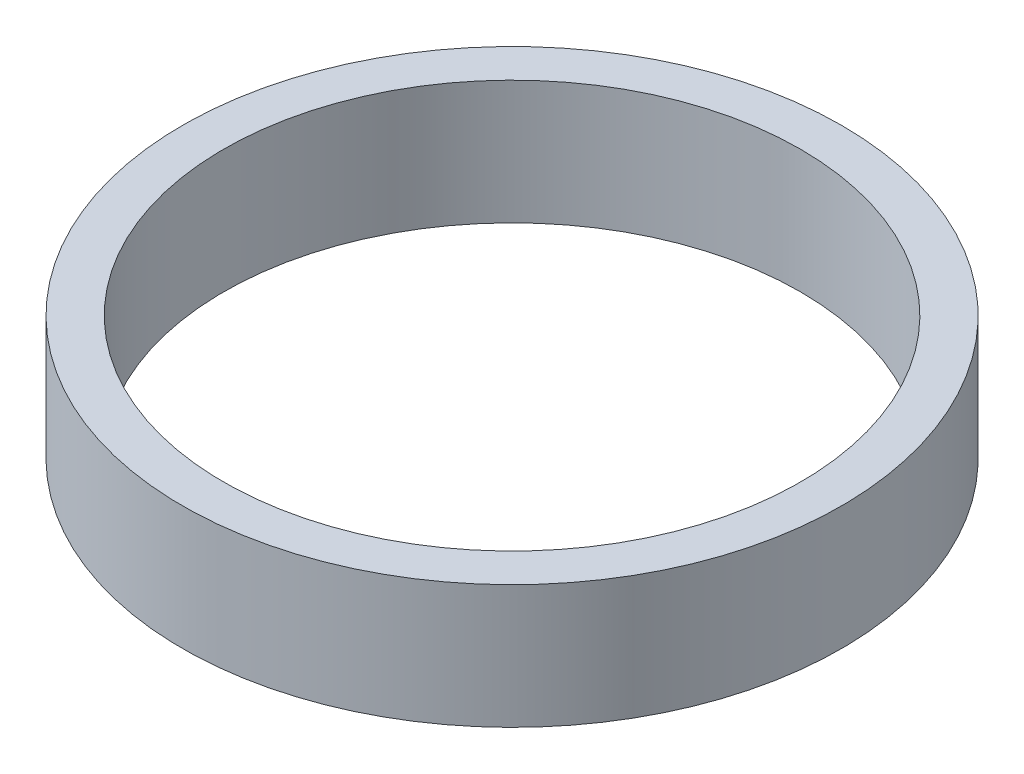
SolidWorks part; units mm, degrees
ref_plane "Front Plane" through (0, 0, 0) normal (0, 0, 1) x (1, 0, 0)
ref_plane "Top Plane" through (0, 0, 0) normal (0, 1, 0) x (1, 0, 0)
ref_plane "Right Plane" through (0, 0, 0) normal (1, 0, 0) x (0, 0, -1)
sketch "Sketch2" plane through (0, 0, 0) normal (0, 1, 0) x (1, 0, 0)
  circle A0 centre (0, 0) radius 20.32
  circle A1 centre (0, 0) radius 17.78
  dimension "1.5" = 40.64
  dimension "D2" = 35.56
extrude "Boss-Extrude1" add sketch "Sketch2" along normal blind 7.62
